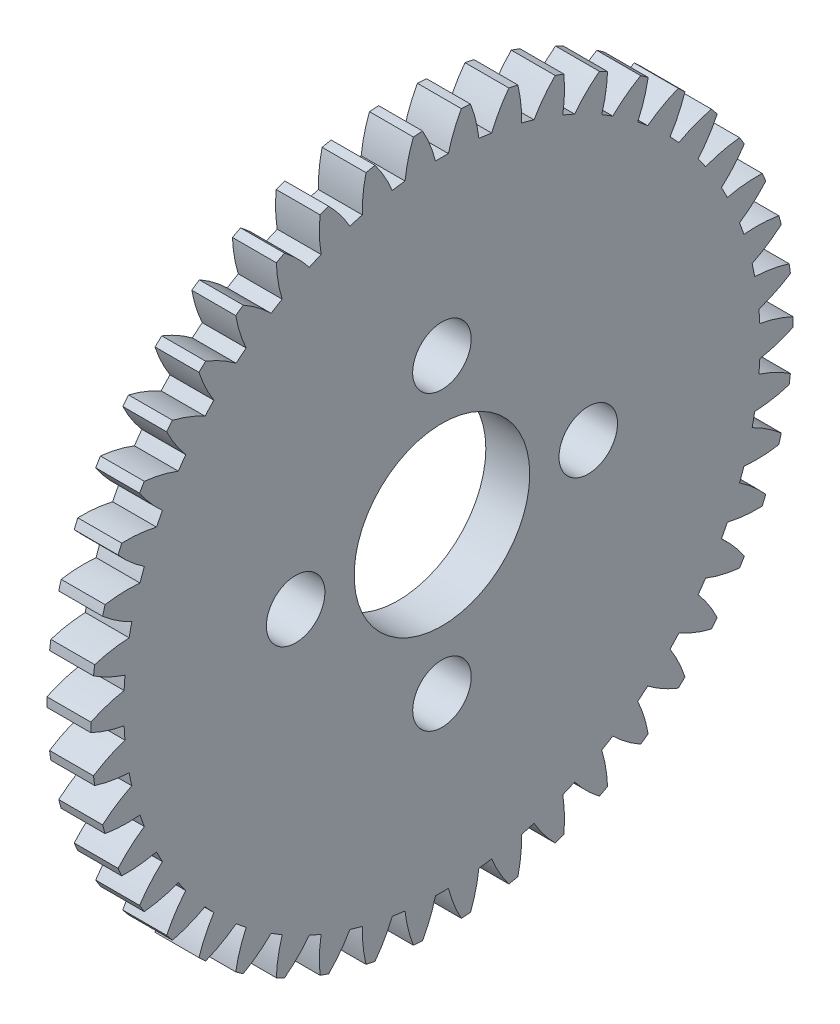
SolidWorks part; units mm, degrees
ref_plane "Plane1" through (0, 0, 0) normal (0, 0, 1) x (1, 0, 0)
ref_plane "Plane2" through (0, 0, 0) normal (0, 1, 0) x (1, 0, 0)
ref_plane "Plane3" through (0, 0, 0) normal (1, 0, 0) x (0, 0, -1)
other "Configuration Table"
sketch "HoldingSke" plane through (0, 0, 0) normal (0, 1, 0) x (1, 0, 0)
  line L0 (0, 0) -> (1.3893, -1.4387)
  line L1 (-15, 0) -> (100, 0) construction
  line L2 (0, 0) -> (-2.1039, 2.3779)
  line L3 (0, 0) -> (-11.863, 4.5341)
  line L4 (0, 0) -> (5.9991, 6.2122)
  line L5 (0, 0) -> (-3.1856, -1.1881)
  line L6 (0, 0) -> (-1.2434, -0.839)
  line L7 (-2.1039, 2.3779) -> (-1.372, 5.6982)
  line L8 (-76.2, 54.61) -> (-75.9, 54.61)
  line L9 (-71.009, 38.7566) -> (-53.1078, 45.2721)
  line L10 (-76.2, 71.12) -> (104.1128, 71.12)
  line L11 (0, 0) -> (-1.5, 0)
  line L12 (-76.2, 101.6) -> (-76.181, 101.6)
  line L13 (24.9733, 27.94) -> (52.9518, 28.4284)
  line L14 (24.9733, 27.94) -> (24.9743, 27.94)
  line L15 (24.9733, 27.94) -> (100.4006, 29.5858)
  line L16 (-63.627, -0.5) -> (-12.827, -0.5)
  circle A0 centre (0, 0) radius 1
  circle A1 centre (0, 0) radius 2.3
  circle A2 centre (0, 0) radius 2.3
  circle A3 centre (0, 0) radius 1
  dimension "MHD" = 4.6
  dimension "Hub_dia" = 4.6
  dimension "Bore" = 2
  dimension "MBD" = 2
  dimension "Num_teeth" = 46
  dimension "Pitch" = 2
  dimension "Overall_len" = 3.4
  dimension "Show_teeth" = 46
  dimension "Thickness" = 1.5
  dimension "OAL" = 3.4001
  dimension "T_dim" = 0.3
  dimension "Ap" = 20
  dimension "H" = 19.05
  dimension "Pitch_radius" = 180.3128
  dimension "Width" = 1.5
  dimension "Backlash" = 0.019
  dimension "Addendum_fac" = 1
  dimension "Dedendum_fac" = 1.25
  dimension "Clearance_fac" = 0.25
  dimension "Dedendum_add" = 0.001
  dimension "Module" = 0.5
sketch "BasProSke" plane through (0, 0, 0) normal (0, 1, 0) x (1, 0, 0)
  line L0 (-10, 0) -> (60, 0) construction
  line L1 (0, 0) -> (0, 12)
  line L2 (0, 0) -> (1.5, 0)
  line L3 (1.5, 0) -> (1.5, 12)
  line L4 (1.5, 12) -> (0, 12)
  dimension "Thickness" = 1.5
  dimension "Diameter" = 24
revolve "Base-Revolve" add sketch "BasProSke" angle 360 about L0
sketch "TooCutSke" plane through (0, 0, 0) normal (1, 0, 0) x (0, 0, -1)
  line L1 (0, 0) -> (0, 107) construction
  line L2 (0, 0) -> (-0.4259, 11.4921) construction
  line L3 (0, 0) -> (-1.5688, 22.9352) construction
  line L4 (-0.4259, 11.4921) -> (-0.7844, 11.4676) construction
  arc A0 (0.2206, 10.8718) -> (-0.2206, 10.8718) centre (0, 0) ccw
  arc A1 (0.6761, 12.0064) -> (-0.6761, 12.0064) centre (0, 0) ccw
  circle A2 centre (0, 0) radius 11.5 construction
  circle A3 centre (0, 0) radius 10.8065 construction
  arc A4 (-0.2206, 10.8718) -> (-0.6761, 12.0064) centre (-4.6794, 9.7408) ccw
  arc A5 (0.6761, 12.0064) -> (0.2206, 10.8718) centre (4.6794, 9.7408) ccw
  dimension "Root_dia" = 21.748
  dimension "Overcut_dia" = 24.0508
  dimension "Pitch_dia" = 23
  dimension "Base_dia" = 21.6129
  dimension "Flank_rad" = 4.6
  dimension "Half_ang" = 3.913
  dimension "Half_CT" = 0.3594
extrude "ToothCut" cut sketch "TooCutSke" along normal through all
fillet "Breaks" [suppressed] radius 0.01
fillet "RootFillets" [suppressed] radius 0.126
pattern_circular "TeethCuts" count 46 every 7.826 about axis through (-10, 0, 0) along (1, 0, 0) of "ToothCut", "RootFillets", "Breaks"
sketch "HubNeaOneSke" plane through (0, 0, 0) normal (-1, 0, 0) x (0, 0, 1)
  circle A0 centre (0, 0) radius 2.3
  dimension "Diameter" = 4.6
extrude "HubNearOne" add sketch "HubNeaOneSke" along normal blind 1.9001
sketch "HubNeaBotSke" plane through (0, 0, 0) normal (-1, 0, 0) x (0, 0, 1)
  circle A0 centre (0, 0) radius 2.3
  dimension "Diameter" = 4.6
extrude "HubNearBoth" [suppressed] add sketch "HubNeaBotSke" along normal blind 0.95
ref_plane "FarPln" through (1.5, 0, 0) normal (1, 0, 0) x (0, 0, -1)
sketch "HubFarSke" plane through (1.5, 0, 0) normal (1, 0, 0) x (0, 0, -1)
  circle A0 centre (0, 0) radius 2.3
  dimension "Diameter" = 4.6
extrude "HubFar" [suppressed] add sketch "HubFarSke" along normal blind 0.95
sketch "BorSke" plane through (0, 0, 0) normal (1, 0, 0) x (0, 0, -1)
  circle A0 centre (0, 0) radius 1
  dimension "Diameter" = 2
extrude "Bore" cut sketch "BorSke" along normal mid plane 6.8001
sketch "KeySke" plane through (0, 0, 0) normal (1, 0, 0) x (0, 0, -1)
  line L0 (-0.4, 0) -> (-0.4, 1.3)
  line L1 (-0.4, 1.3) -> (0.4, 1.3)
  line L2 (0.4, 1.3) -> (0.4, 0)
  line L3 (0, 0) -> (0, 34) construction
  line L4 (-0.4, 0) -> (0.4, 0)
  dimension "Offset" = 1.3
  dimension "Width" = 0.8
extrude "Keyway" [suppressed] cut sketch "KeySke" along normal mid plane 6.8001
pattern_circular "Keyway2" [suppressed] count 2 every 90 about axis through (-10, 0, 0) along (1, 0, 0)
ref_plane "Plane4" through (0.75, 0, 0) normal (-1, 0, 0) x (0, 0, 1)
sketch "Sketch1" plane through (1.5, 0, 0) normal (1, 0, 0) x (0, 0, -1)
  circle A0 centre (0, 0) radius 3
  dimension "D1" = 6
extrude "Cut-Extrude1" cut sketch "Sketch1" against normal through all
sketch "Sketch2" plane through (1.5, 0, 0) normal (1, 0, 0) x (0, 0, -1)
  circle A0 centre (0, 0) radius 6 construction
  circle A1 centre (0, 5) radius 1
  point P5 (0, 0)
  point P6 (0, 0)
  dimension "D1" = 12
  dimension "D2" = 2
  dimension "D3" = 5
extrude "Cut-Extrude2" cut sketch "Sketch2" against normal through all
pattern_circular "CirPattern1" count 4 over 360 about axis through (0, 0, 0) along (1, 0, 0) of "Cut-Extrude2"
equation "' \"Module@HoldingSke\" = 6.35"
equation "' \"Num_teeth@HoldingSke\" = 12"
equation "' \"Ap@HoldingSke\" =  20"
equation "' \"Ap@HoldingSke\" = 20"
equation "' \"Width@HoldingSke\" = 0.5 * 25.4"
equation "' \"Hub_dia@HoldingSke\"= 1 * 25.4"
equation "' \"Hub_dia@HoldingSke\" = 1 * 25.4"
equation "' \"Overall_len@HoldingSke\" = 1.0 * 25.4"
equation "' \"Bore@HoldingSke\" = 0.75 * 25.4"
equation "' \"T_dim@HoldingSke\" = 0.1 * 25.4"
equation "' \"Width@KeySke\" = 0.25 * 25.4"
equation "' \"Show_teeth@HoldingSke\" = 13"
equation "' \"Backlash@HoldingSke\" = 0.009 * 25.4"
equation "' \"Addendum_fac@HoldingSke\" = 1.0"
equation "' \"Dedendum_fac@HoldingSke\" = 1.25"
equation "' \"Dedendum_add@HoldingSke\" = 0.00005 * 25.4"
equation "' \"Clearance_fac@HoldingSke\" = 0.25"
equation "\"Pitch@HoldingSke\" = 1 / \"Module@HoldingSke\""
equation "\"Overcut_dia@TooCutSke\" = (\"Num_teeth@HoldingSke\" + 2 * \"Addendum_fac@HoldingSke\") / \"Pitch@HoldingSke\" + 0.002 * 25.4"
equation "\"Pitch_dia@TooCutSke\" = \"Num_teeth@HoldingSke\" / \"Pitch@HoldingSke\""
equation "\"Base_dia@TooCutSke\" = \"Num_teeth@HoldingSke\" / \"Pitch@HoldingSke\" * cos((\"Ap@HoldingSke\"  * 3.14159265 / 180))"
equation "\"Root_dia@TooCutSke\" = (\"Num_teeth@HoldingSke\" + 2) / \"Pitch@HoldingSke\" - 2 * (\"Addendum_fac@HoldingSke\" + \"Dedendum_fac@HoldingSke\") / \"Pitch@HoldingSke\" - \"Dedendum_add@HoldingSke\" * 2"
equation "\"Half_ang@TooCutSke\" = 180 / \"Num_teeth@HoldingSke\""
equation "\"Half_CT@TooCutSke\" = \"Num_teeth@HoldingSke\" / \"Pitch@HoldingSke\" * sin((3.14159265 / 2 / \"Num_teeth@HoldingSke\")) / 2 - 7 * \"Backlash@HoldingSke\" / 4"
equation "\"Flank_rad@TooCutSke\" = \"Num_teeth@HoldingSke\" / \"Pitch@HoldingSke\" / 5"
equation "\"Radius@RootFillets\" = \"Clearance_fac@HoldingSke\" / \"Pitch@HoldingSke\" + \"Dedendum_add@HoldingSke\""
equation "\"Break_rad@Breaks\" = 0.02 / \"Pitch@HoldingSke\""
equation "\"Thickness@HoldingSke\" = \"Width@HoldingSke\""
equation "\"OAL@HoldingSke\" = \"Thickness@HoldingSke\""
equation "\"MHD@HoldingSke\" = (\"Num_teeth@HoldingSke\" + 2) / \"Pitch@HoldingSke\" - 2 * (\"Addendum_fac@HoldingSke\" + \"Dedendum_fac@HoldingSke\")  / \"Pitch@HoldingSke\" - \"Dedendum_add@HoldingSke\" * 2"
equation "\"MBD@HoldingSke\" = (\"Num_teeth@HoldingSke\" + 2) / \"Pitch@HoldingSke\" - 2 * (\"Addendum_fac@HoldingSke\" + \"Dedendum_fac@HoldingSke\")  / \"Pitch@HoldingSke\" - \"Dedendum_add@HoldingSke\" * 2 - 0.002 * 25.4"
equation "\"MHD@HoldingSke\" = ((sgn( \"MHD@HoldingSke\" - \"Hub_dia@HoldingSke\" )-1)*( \"MHD@HoldingSke\" - \"Hub_dia@HoldingSke\" ))/-2+ \"Hub_dia@HoldingSke\""
equation "\"MBD@HoldingSke\" = ((sgn( \"MBD@HoldingSke\" - \"Bore@HoldingSke\" )-1)*( \"MBD@HoldingSke\" - \"Bore@HoldingSke\" ))/-2+ \"Bore@HoldingSke\""
equation "\"OAL@HoldingSke\" = ((sgn( \"OAL@HoldingSke\" - \"Overall_len@HoldingSke\" )+1)*( \"OAL@HoldingSke\" - \"Overall_len@HoldingSke\" ))/2 + \"Overall_len@HoldingSke\" + 0.000002 * 25.4"
equation "\"Num_teeth@TeethCuts\" = int( \"Show_teeth@HoldingSke\" ) + 1"
equation "\"Num_teeth@TeethCuts\" = ((sgn( \"Num_teeth@TeethCuts\" - \"Num_teeth@HoldingSke\" )-1)*( \"Num_teeth@TeethCuts\" - \"Num_teeth@HoldingSke\" ))/-2+ \"Num_teeth@HoldingSke\""
equation "\"Num_teeth@TeethCuts\" = ((sgn( \"Num_teeth@TeethCuts\" - 2.0)+1)*( \"Num_teeth@TeethCuts\" - 2.0))/2 +2.0"
equation "\"Angle@TeethCuts\" = 360.0 / \"Num_teeth@HoldingSke\""
equation "\"Diameter@BasProSke\" = (\"Num_teeth@HoldingSke\" + 2 * \"Addendum_fac@HoldingSke\") / \"Pitch@HoldingSke\""
equation "\"Thickness@BasProSke\"  = \"Thickness@HoldingSke\""
equation "' \"Fillet_rad@BasProSke\" =  \"Thickness@HoldingSke\" * 0.05"
equation "' \"Fillet_rad@BasProSke\" = \"Thickness@HoldingSke\" * 0.05"
equation "\"MHD@HoldingSke\" = ((sgn( \"MHD@HoldingSke\" - \"Root_dia@TooCutSke\" )-1)*( \"MHD@HoldingSke\" - \"Root_dia@TooCutSke\" ))/-2+ \"Root_dia@TooCutSke\""
equation "\"Diameter@HubNeaOneSke\" = \"MHD@HoldingSke\""
equation "\"Length@HubNearOne\" = \"OAL@HoldingSke\" - \"Thickness@BasProSke\""
equation "\"Diameter@HubNeaBotSke\" = \"MHD@HoldingSke\""
equation "\"Length@HubNearBoth\" = ( \"OAL@HoldingSke\" - \"Thickness@BasProSke\" ) / 2.0"
equation "\"Thickness@FarPln\" = \"Thickness@BasProSke\""
equation "\"Diameter@HubFarSke\" = \"MHD@HoldingSke\""
equation "\"Length@HubFar\" = ( \"OAL@HoldingSke\" - \"Thickness@BasProSke\" ) / 2.0"
equation "\"Diameter@BorSke\" = \"MBD@HoldingSke\""
equation "\"D1@Bore\" = \"OAL@HoldingSke\" * 2.0"
equation "\"D1@Keyway\" = \"OAL@HoldingSke\" * 2.0"
equation "\"Offset@KeySke\" = \"T_dim@HoldingSke\" + \"MBD@HoldingSke\" / 2.0"
